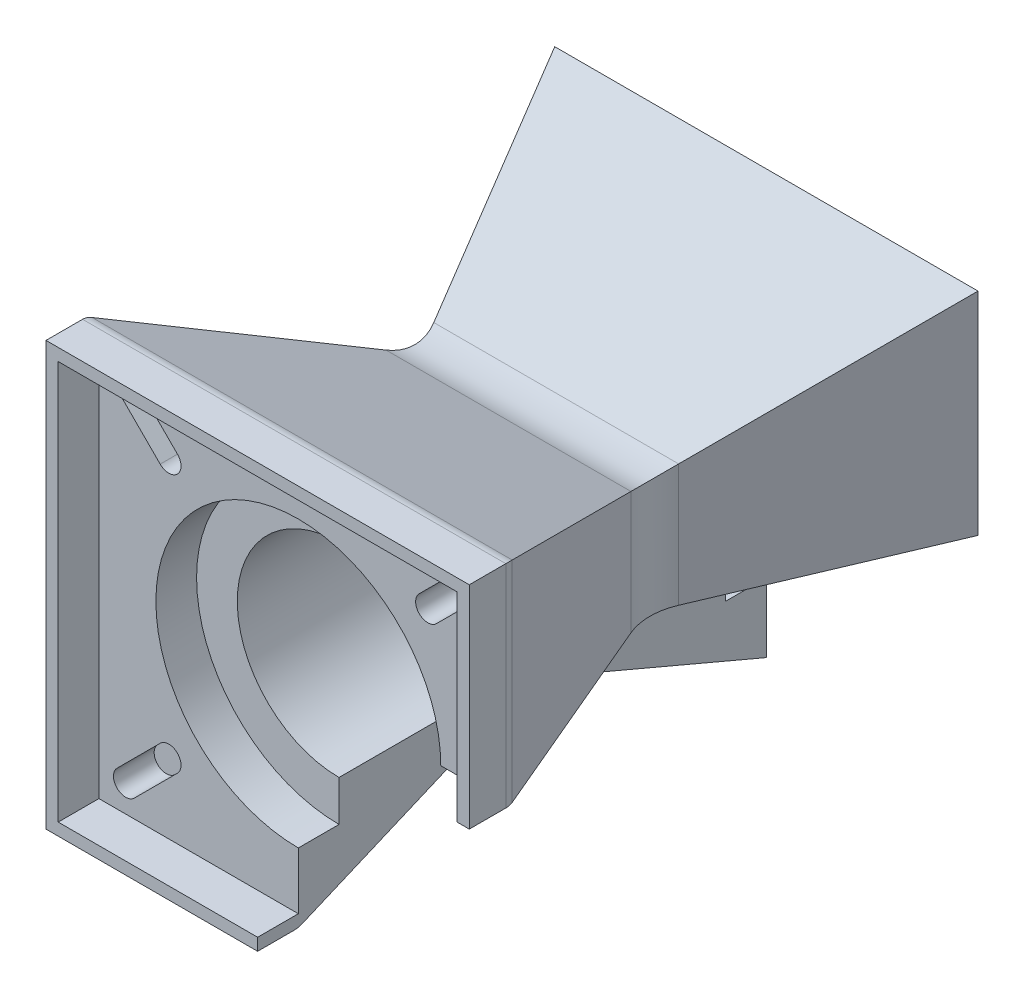
SolidWorks part; units mm, degrees
material "Cast Stainless Steel"
ref_plane "Front Plane" through (0, 0, 0) normal (0, 0, 1) x (1, 0, 0)
ref_plane "Top Plane" through (0, 0, 0) normal (0, 1, 0) x (1, 0, 0)
ref_plane "Right Plane" through (0, 0, 0) normal (1, 0, 0) x (0, 0, -1)
sketch "Sketch2" plane through (0, 0, 0) normal (0, 0, 1) x (1, 0, 0)
  line L1 (-52, -52) -> (52, -52)
  line L2 (-52, -52) -> (-52, 52)
  line L3 (-52, 52) -> (52, 52)
  line L4 (52, -52) -> (52, 52)
  line L5 (-52, -52) -> (52, 52) construction
  line L6 (-52, 52) -> (52, -52) construction
  point P0 (0, 0)
  dimension "D1" = 104
  dimension "D2" = 104
extrude "Boss-Extrude1" add sketch "Sketch2" along normal blind 57.5 draft 23
mirror "Mirror1" about plane through (0, 0, 57.5) normal (0, 0, -1) of "Boss-Extrude1"
sketch "Sketch3" plane through (0, 0, 115) normal (0, 0, 1) x (1, 0, 0)
  circle A0 centre (0, 0) radius 25
  dimension "D1" = 50
extrude "Cut-Extrude1" cut sketch "Sketch3" against normal blind 240.5
sketch "Sketch5" plane through (0, 0, 115) normal (0, 0, 1) x (1, 0, 0)
  line L0 (0, -62.5968) -> (0, 62.5968) construction
  line L1 (102.9009, 0) -> (-102.9009, 0) construction
  line L2 (0, 0) -> (52, 0)
  line L3 (52, -52) -> (52, 52) construction
  line L4 (52, 0) -> (52, -52)
  line L5 (52, -52) -> (0, -52)
  line L6 (-52, -52) -> (52, -52) construction
  line L7 (0, -52) -> (0, 0)
  point P5 (0, 0)
  point P9 (0, 0)
extrude "Cut-Extrude2" cut sketch "Sketch5" against normal blind 240.5
sketch "Sketch6" plane through (0, 0, 115) normal (0, 0, 1) x (1, 0, 0)
  circle A0 centre (0, 0) radius 35
  dimension "D1" = 70
extrude "Cut-Extrude3" cut sketch "Sketch6" against normal blind 10
sketch "Sketch7" plane through (0, 0, 0) normal (0, 0, -1) x (-1, 0, 0)
  circle A0 centre (0, 0) radius 35
  dimension "D1" = 70
extrude "Cut-Extrude4" cut sketch "Sketch7" against normal blind 10
fillet "Fillet1" radius 15 4 edges at (-27.5927, 0, 57.5) (-13.7963, -27.5927, 57.5) (27.5927, 13.7963, 57.5) (0, 27.5927, 57.5)
sketch "Sketch8" plane through (0, 0, 115) normal (0, 0, 1) x (1, 0, 0)
  line L0 (0, -52) -> (-52, -52)
  line L1 (-52, -52) -> (-52, 52)
  line L2 (-52, 52) -> (52, 52)
  line L3 (52, 52) -> (52, 0)
  line L4 (0, -49) -> (-49, -49)
  line L5 (0, -35) -> (0, -52) construction
  line L6 (-49, -49) -> (-49, 49)
  line L7 (-49, 49) -> (49, 49)
  line L8 (49, 49) -> (49, 0)
  line L9 (52, 0) -> (35, 0) construction
  line L10 (49, 0) -> (52, 0)
  line L11 (0, -49) -> (0, -52)
  dimension "D1" = 3
  dimension "D2" = 3
  dimension "D3" = 3
  dimension "3" = 3
extrude "Boss-Extrude2" add sketch "Sketch8" along normal blind 10
sketch "Sketch10" plane through (0, 0, 115) normal (0, 0, 1) x (1, 0, 0)
  line L0 (0, -77.2421) -> (0, 77.2421) construction
  line L1 (97.2613, 0) -> (-97.2613, 0) construction
  line L2 (52, -52) -> (-52, 52) construction
  line L3 (-42.4264, 42.4264) -> (-31.8198, 31.8198) construction
  line L4 (-40.3051, 44.5477) -> (-29.6985, 33.9411)
  line L5 (-44.5477, 40.3051) -> (-33.9411, 29.6985)
  line L6 (42.4264, 42.4264) -> (31.8198, 31.8198) construction
  line L7 (44.5477, 40.3051) -> (33.9411, 29.6985)
  line L8 (40.3051, 44.5477) -> (29.6985, 33.9411)
  line L9 (42.4264, -42.4264) -> (31.8198, -31.8198) construction
  line L10 (40.3051, -44.5477) -> (29.6985, -33.9411)
  line L11 (44.5477, -40.3051) -> (33.9411, -29.6985)
  line L12 (-42.4264, -42.4264) -> (-31.8198, -31.8198) construction
  line L13 (-44.5477, -40.3051) -> (-33.9411, -29.6985)
  line L14 (-40.3051, -44.5477) -> (-29.6985, -33.9411)
  arc A0 (-40.3051, 44.5477) -> (-44.5477, 40.3051) centre (-42.4264, 42.4264) ccw
  arc A1 (-33.9411, 29.6985) -> (-29.6985, 33.9411) centre (-31.8198, 31.8198) ccw
  circle A2 centre (0, 0) radius 50
  arc A3 (44.5477, 40.3051) -> (40.3051, 44.5477) centre (42.4264, 42.4264) ccw
  arc A4 (29.6985, 33.9411) -> (33.9411, 29.6985) centre (31.8198, 31.8198) ccw
  arc A5 (40.3051, -44.5477) -> (44.5477, -40.3051) centre (42.4264, -42.4264) ccw
  arc A6 (33.9411, -29.6985) -> (29.6985, -33.9411) centre (31.8198, -31.8198) ccw
  arc A7 (-44.5477, -40.3051) -> (-40.3051, -44.5477) centre (-42.4264, -42.4264) ccw
  arc A8 (-29.6985, -33.9411) -> (-33.9411, -29.6985) centre (-31.8198, -31.8198) ccw
  point P5 (0, 0)
  point P9 (0, 0)
  point P12 (0, 0)
  point P15 (-37.1231, 37.1231)
  point P25 (37.1231, 37.1231)
  point P32 (37.1231, -37.1231)
  point P39 (-37.1231, -37.1231)
  dimension "D2" = 3
  dimension "D3" = 45
  dimension "D4" = 100
  dimension "D1" = 15
  dimension "D5" = 4
extrude "Cut-Extrude5" cut sketch "Sketch10" against normal blind 10 contours L5 A1 L4 A0 | L7 A4 L8 A3 | L14 A8 L13 A7
fillet "Fillet2" radius 5 4 edges at (52, 26, 115) (0, 52, 115) (-52, 0, 115) (-26, -52, 115)
